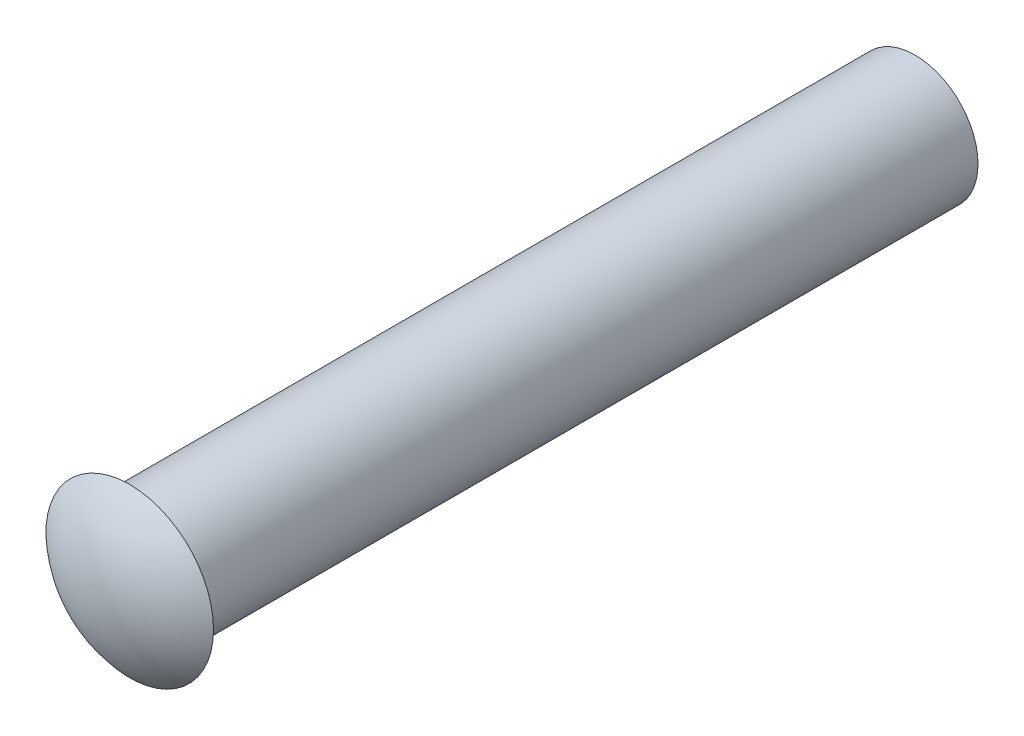
SolidWorks part; units mm, degrees
ref_plane "Front Plane" through (0, 0, 0) normal (0, 0, 1) x (1, 0, 0)
ref_plane "Top Plane" through (0, 0, 0) normal (0, 1, 0) x (1, 0, 0)
ref_plane "Right Plane" through (0, 0, 0) normal (1, 0, 0) x (0, 0, -1)
sketch "Sketch1" plane through (0, 0, 0) normal (1, 0, 0) x (0, 0, -1)
  line L0 (0, 0) -> (19.812, 0)
  line L1 (19.812, 0) -> (19.812, 1.524)
  line L2 (19.812, 1.524) -> (0.762, 1.524)
  line L6 (0.762, 1.524) -> (0.762, 2.032)
  arc A1 (0, 0) -> (0.762, 2.032) centre (3.0903, 0) cw
  dimension "D1" = 1.524
  dimension "D2" = 19.05
revolve "Revolve1" add sketch "Sketch1" angle 360 about L0
